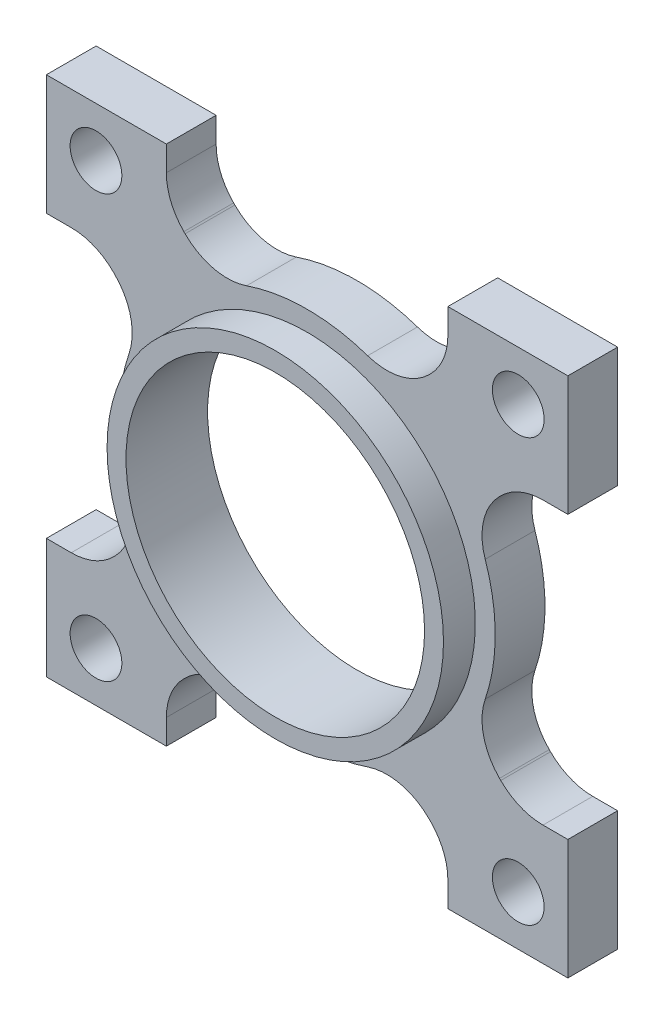
SolidWorks part; units mm, degrees
ref_plane "Front Plane" through (0, 0, 0) normal (0, 0, 1) x (1, 0, 0)
ref_plane "Top Plane" through (0, 0, 0) normal (0, 1, 0) x (1, 0, 0)
ref_plane "Right Plane" through (0, 0, 0) normal (1, 0, 0) x (0, 0, -1)
sketch "Sketch3" plane through (0, 0, 0) normal (0, 0, 1) x (1, 0, 0)
  line L0 (-13.4709, -13.4709) -> (13.4709, -13.4709) construction
  line L1 (16.637, 16.637) -> (-16.637, 16.637)
  line L2 (16.637, 16.637) -> (16.637, -16.637)
  line L3 (16.637, -16.637) -> (-16.637, -16.637)
  line L4 (-16.637, 16.637) -> (-16.637, -16.637)
  line L5 (16.637, 16.637) -> (-16.637, -16.637) construction
  line L6 (16.637, -16.637) -> (-16.637, 16.637) construction
  line L7 (13.4709, -13.4709) -> (13.4709, 13.4709) construction
  line L8 (13.4709, 13.4709) -> (-13.4709, 13.4709) construction
  line L9 (-13.4709, 13.4709) -> (-13.4709, -13.4709) construction
  circle A0 centre (0, 0) radius 9.525
  circle A1 centre (-13.4709, 13.4709) radius 1.651
  circle A2 centre (-13.4709, -13.4709) radius 1.651
  circle A3 centre (13.4709, 13.4709) radius 1.651
  circle A4 centre (13.4709, -13.4709) radius 1.651
  point P0 (0, 0)
  dimension "D2" = 19.05
  dimension "D4" = 3.302
  dimension "D1" = 33.274
  dimension "D3" = 26.9418
extrude "Boss-Extrude1" add sketch "Sketch3" along normal blind 3.175
sketch "Sketch4" plane through (0, 0, 3.175) normal (0, 0, 1) x (1, 0, 0)
  line L0 (-8.9808, 16.637) -> (-8.9808, 13.4709)
  line L1 (16.637, 16.637) -> (-16.637, 16.637) construction
  line L2 (-8.9808, 13.4709) -> (-5.9389, 10.4291)
  line L3 (-16.637, 8.9808) -> (-13.4709, 8.9808)
  line L4 (-16.637, 16.637) -> (-16.637, -16.637) construction
  line L5 (-13.4709, 8.9808) -> (-10.4291, 5.9389)
  line L6 (-16.637, -8.9808) -> (-13.4709, -8.9808)
  line L7 (-13.4709, -8.9808) -> (-10.4291, -5.9389)
  line L8 (-8.9808, -16.637) -> (-8.9808, -13.4709)
  line L9 (-16.637, -16.637) -> (16.637, -16.637) construction
  line L10 (-8.9808, -13.4709) -> (-5.9389, -10.4291)
  line L11 (8.9808, -16.637) -> (8.9808, -13.4709)
  line L12 (8.9808, -13.4709) -> (5.9389, -10.4291)
  line L13 (16.637, -8.9808) -> (13.4709, -8.9808)
  line L14 (16.637, -16.637) -> (16.637, 16.637) construction
  line L15 (13.4709, -8.9808) -> (10.4291, -5.9389)
  line L16 (8.9808, 16.637) -> (8.9808, 13.4709)
  line L17 (8.9808, 13.4709) -> (5.9389, 10.4291)
  line L18 (16.637, 8.9808) -> (13.4709, 8.9808)
  line L19 (13.4709, 8.9808) -> (10.4291, 5.9389)
  line L20 (-13.4709, 8.9808) -> (-8.9808, 13.4709) construction
  line L21 (8.9808, 13.4709) -> (13.4709, 8.9808) construction
  line L22 (8.9808, -13.4709) -> (13.4709, -8.9808) construction
  line L23 (-13.4709, -8.9808) -> (-8.9808, -13.4709) construction
  line L24 (-13.4709, 8.9808) -> (-13.4709, 16.637) construction
  line L25 (-8.9808, 13.4709) -> (-16.637, 13.4709) construction
  line L26 (-13.4709, 13.4709) -> (-13.4709, -13.4709) construction
  line L27 (-8.9808, 16.637) -> (8.9808, 16.637)
  line L28 (16.637, 8.9808) -> (16.637, -8.9808)
  line L29 (-16.637, 8.9808) -> (-16.637, -8.9808)
  line L30 (-8.9808, -16.637) -> (8.9808, -16.637)
  circle A0 centre (0, 0) radius 12.0015 construction
  arc A1 (-10.4291, 5.9389) -> (-10.4291, -5.9389) centre (0, 0) ccw
  arc A2 (-5.9389, -10.4291) -> (5.9389, -10.4291) centre (0, 0) ccw
  arc A3 (10.4291, -5.9389) -> (10.4291, 5.9389) centre (0, 0) ccw
  arc A4 (-5.9389, 10.4291) -> (5.9389, 10.4291) centre (0, 0) cw
  dimension "D2" = 24.003
  dimension "D1" = 6.35
extrude "Cut-Extrude1" cut sketch "Sketch4" against normal through all
sketch "Sketch5" plane through (0, 0, 3.175) normal (0, 0, 1) x (1, 0, 0)
  circle A0 centre (0, 0) radius 9.525
  circle A1 centre (0, 0) radius 10.7315
  circle A2 centre (0, 0) radius 9.525 construction
  dimension "D1" = 21.463
extrude "Boss-Extrude2" add sketch "Sketch5" along normal blind 2.032
fillet "Fillet1" radius 3.81 16 edges at (-13.4709, -8.9808, 1.5875) (-10.4291, -5.9389, 1.5875) (-13.4709, 8.9808, 1.5875) (-10.4291, 5.9389, 1.5875) (-8.9808, 13.4709, 1.5875) (-5.9389, 10.4291, 1.5875) (5.9389, 10.4291, 1.5875) (8.9808, 13.4709, 1.5875) (13.4709, 8.9808, 1.5875) (10.4291, 5.9389, 1.5875) (10.4291, -5.9389, 1.5875) (13.4709, -8.9808, 1.5875) (8.9808, -13.4709, 1.5875) (5.9389, -10.4291, 1.5875) (-5.9389, -10.4291, 1.5875) (-8.9808, -13.4709, 1.5875)
